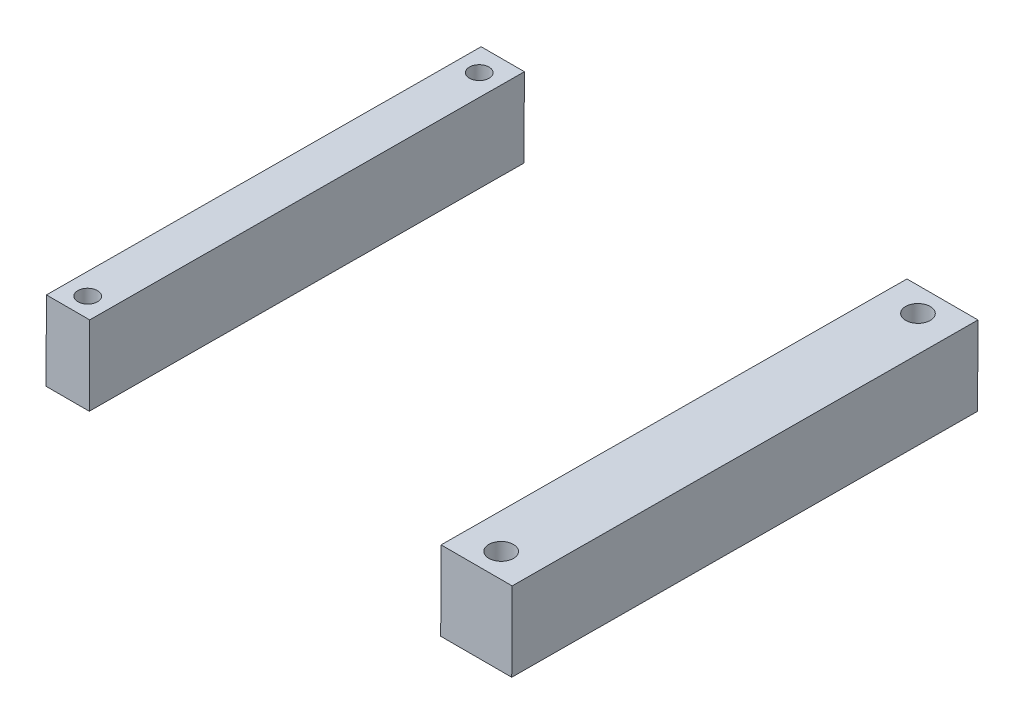
SolidWorks part; units mm, degrees
ref_plane "Front Plane" through (0, 0, 0) normal (0, 0, 1) x (1, 0, 0)
ref_plane "Top Plane" through (0, 0, 0) normal (0, 1, 0) x (1, 0, 0)
ref_plane "Right Plane" through (0, 0, 0) normal (1, 0, 0) x (0, 0, -1)
sketch "Sketch1" plane through (0, 299.9322, -1.6692) normal (0, 1, -0.0056) x (1, 0, 0)
  line L1 (57.5, 1026.6258) -> (80.5, 1026.6258)
  line L2 (57.5, 1026.6258) -> (57.5, 875.8258)
  line L3 (57.5, 875.8258) -> (80.5, 875.8258)
  line L4 (80.5, 1026.6258) -> (80.5, 875.8258)
  line L5 (-76.5, 1022.7858) -> (-62.5, 1022.7858)
  line L6 (-76.5, 1022.7858) -> (-76.5, 882.0582)
  line L7 (-76.5, 882.0582) -> (-62.5, 882.0582)
  line L8 (-62.5, 1022.7858) -> (-62.5, 882.0582)
  circle A0 centre (-69.5, 1015.1658) radius 3.175
  circle A1 centre (-69.5, 888.4082) radius 3.175
  circle A2 centre (69, 883.7633) radius 3.9687
  circle A3 centre (69, 1018.6883) radius 3.9688
  dimension "D1" = 7.9375
  dimension "D2" = 7.9375
  dimension "D3" = 6.35
  dimension "D4" = 6.35
extrude "Boss-Extrude1" add sketch "Sketch1" along normal blind 25.55
